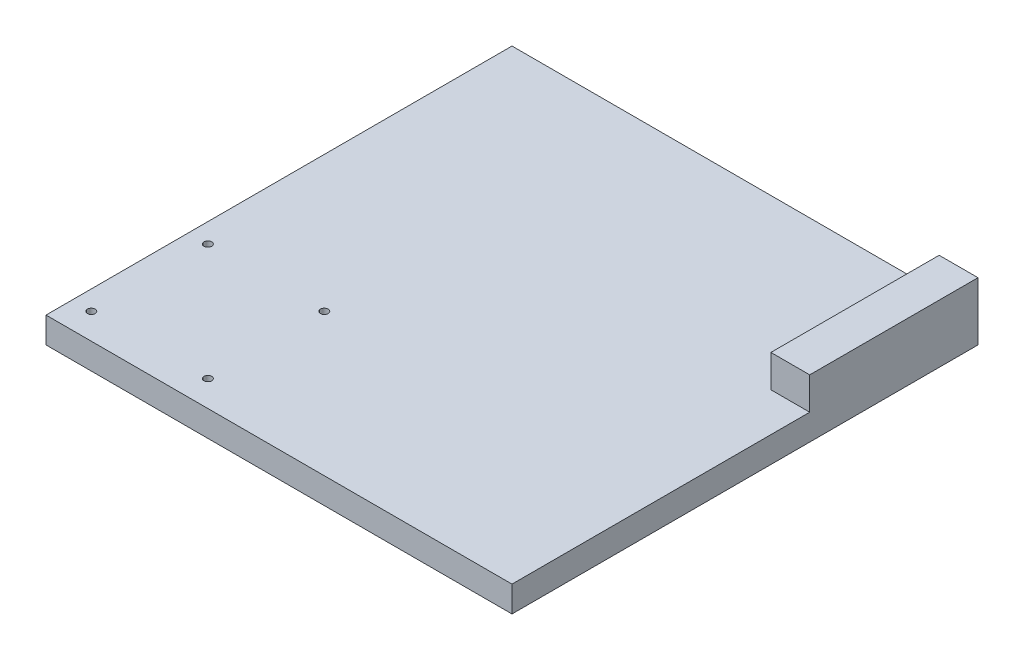
SolidWorks part; units mm, degrees
ref_plane "前视基准面" through (0, 0, 0) normal (0, 0, 1) x (1, 0, 0)
ref_plane "上视基准面" through (0, 0, 0) normal (0, 1, 0) x (1, 0, 0)
ref_plane "右视基准面" through (0, 0, 0) normal (1, 0, 0) x (0, 0, -1)
other "Configuration Table"
sketch "草图1" plane through (0, 0, 0) normal (0, 1, 0) x (1, 0, 0)
  line L0 (0, 0) -> (360, 0)
  line L1 (360, 0) -> (360, 360)
  line L2 (360, 360) -> (0, 360)
  line L3 (0, 360) -> (0, 0)
  dimension "D1" = 360
  dimension "D2" = 360
extrude "凸台-拉伸1" add sketch "草图1" along normal blind 20
sketch "草图2" plane through (0, 20, 0) normal (0, 1, 0) x (1, 0, 0)
  line L0 (0, 360) -> (0, 330)
  line L1 (0, 330) -> (130, 330)
  line L2 (130, 330) -> (130, 360)
  line L3 (360, 360) -> (0, 360) construction
  line L4 (130, 360) -> (0, 360)
  dimension "D1" = 130
  dimension "D2" = 30
sketch "草图4" plane through (0, 20, 0) normal (0, 1, 0) x (1, 0, 0)
  line L0 (360, 360) -> (360, 230)
  line L1 (360, 0) -> (360, 360) construction
  line L2 (360, 230) -> (330, 230)
  line L3 (330, 230) -> (330, 360)
  line L4 (360, 360) -> (0, 360) construction
  line L5 (330, 360) -> (360, 360)
  dimension "D1" = 30
  dimension "D2" = 130
extrude "凸台-拉伸3" add sketch "草图4" along normal blind 25
sketch "草图5" plane through (0, 20, 0) normal (0, 1, 0) x (1, 0, 0)
  line L0 (0, 360) -> (0, 0) construction
  line L1 (0, 0) -> (360, 0) construction
  circle A0 centre (15, 110) radius 3
  circle A1 centre (105, 110) radius 3
  circle A2 centre (15, 20) radius 3
  circle A3 centre (105, 20) radius 3
  dimension "D1" = 6
  dimension "D2" = 6
  dimension "D3" = 6
  dimension "D4" = 6
  dimension "D5" = 15
  dimension "D6" = 90
  dimension "D8" = 90
  dimension "D7" = 90
  dimension "D9" = 20
extrude "切除-拉伸2" cut sketch "草图5" against normal blind 25
